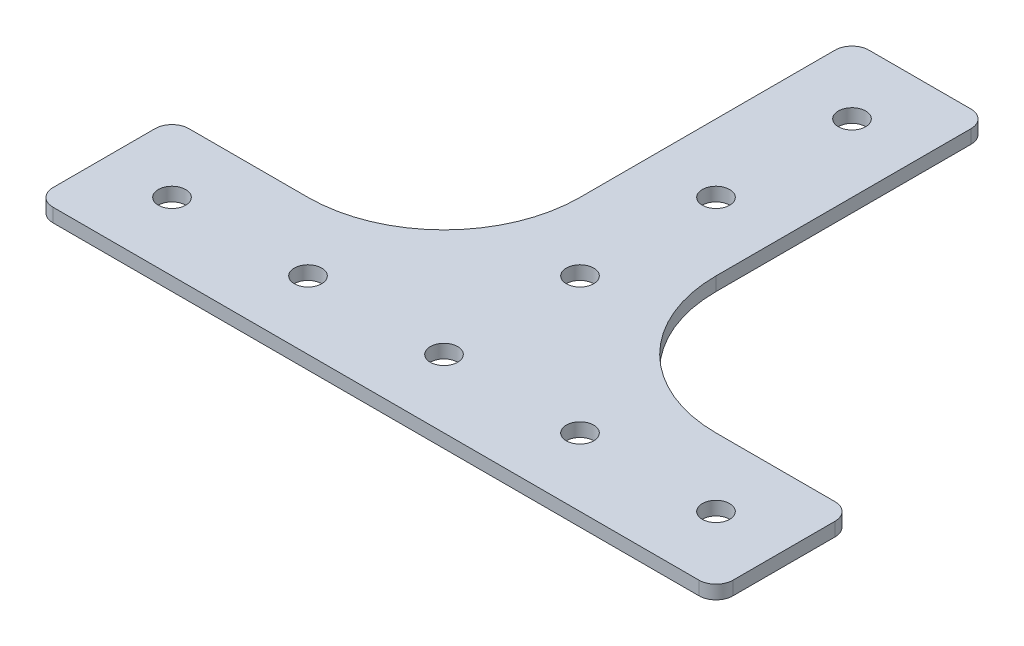
SolidWorks part; units mm, degrees
material "5052-H32"
ref_plane "Front Plane" through (0, 0, 0) normal (0, 0, 1) x (1, 0, 0)
ref_plane "Top Plane" through (0, 0, 0) normal (0, 1, 0) x (1, 0, 0)
ref_plane "Right Plane" through (0, 0, 0) normal (1, 0, 0) x (0, 0, -1)
sketch "Sketch1" plane through (0, 0, 0) normal (0, 1, 0) x (1, 0, 0)
  line L0 (-63.5, 0) -> (63.5, 0)
  line L1 (-63.5, 0) -> (-63.5, 25.4)
  line L2 (-63.5, 25.4) -> (-12.7, 25.4)
  line L3 (-12.7, 25.4) -> (-12.7, 101.6)
  line L4 (-12.7, 101.6) -> (12.7, 101.6)
  line L5 (12.7, 101.6) -> (12.7, 25.4)
  line L6 (12.7, 25.4) -> (63.5, 25.4)
  line L7 (63.5, 25.4) -> (63.5, 0)
  point P4 (0, 0)
  dimension "D1" = 25.4
  dimension "D2" = 127
  dimension "D3" = 101.6
extrude "Boss-Extrude1" add sketch "Sketch1" along normal blind 2.54
fillet "Fillet1" radius 3.175 6 edges at (-63.5, 1.27, -25.4) (-12.7, 1.27, -101.6) (12.7, 1.27, -101.6) (63.5, 1.27, -25.4) (63.5, 1.27, 0) (-63.5, 1.27, 0)
hole_wizard "#7 (0.201) Diameter Hole1" positions "Sketch3" profile "Sketch4" hole size "#7" standard "ANSI Inch" end condition through all
sketch "Sketch3" plane through (0, 2.54, 0) normal (0, 1, 0) x (1, 0, 0)
  line L0 (-60.325, 0) -> (60.325, 0) construction
  line L1 (60.325, 25.4) -> (12.7, 25.4) construction
  point P0 (0, 12.7)
  point P2 (25.4, 12.7)
  point P4 (50.8, 12.7)
  point P6 (-25.4, 12.7)
  point P8 (-50.8, 12.7)
  point P10 (0, 38.1)
  point P12 (0, 63.5)
  point P14 (0, 88.9)
  dimension "D1" = 12.7
  dimension "D2" = 12.7
  dimension "D3" = 25.4
  dimension "D4" = 25.4
  dimension "D5" = 25.4
  dimension "D6" = 25.4
  dimension "D7" = 25.4
  dimension "D8" = 25.4
sketch "Sketch4" plane through (0, 2.54, -12.7) normal (1, 0, 0) x (0, 0, 1)
  line L0 (0, 0) -> (0, 2.54)
  line L1 (0, 2.54) -> (2.5527, 2.54)
  line L2 (2.5527, 2.54) -> (2.5527, 0)
  line L5 (2.5527, 0) -> (0, 0)
  line L11 (0, -6.35) -> (0, 107.95) construction
  dimension "Thru Hole Dia." = 5.1054
  dimension "Thru Hole Depth" = 2.54
fillet "Fillet2" radius 25.4 2 edges at (-12.7, 1.27, -25.4) (12.7, 1.27, -25.4)
